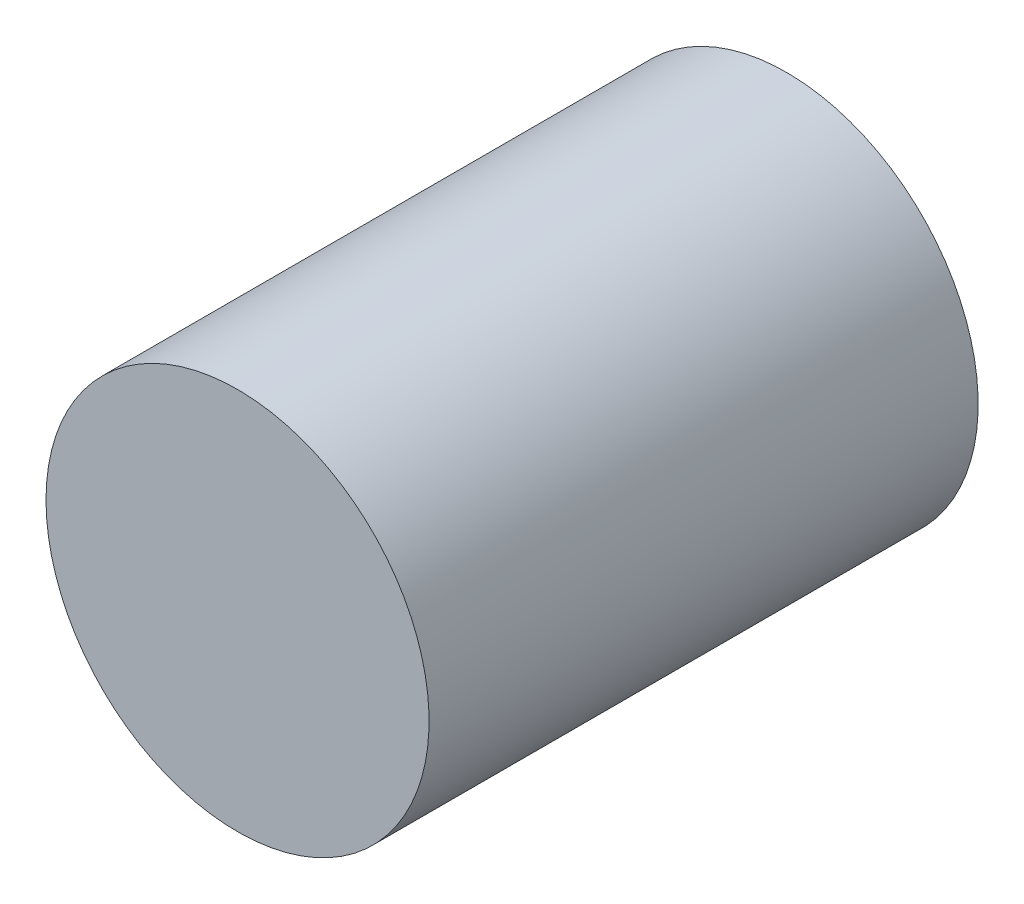
SolidWorks part; units mm, degrees
ref_plane "Front Plane" through (0, 0, 0) normal (0, 0, 1) x (1, 0, 0)
ref_plane "Top Plane" through (0, 0, 0) normal (0, 1, 0) x (1, 0, 0)
ref_plane "Right Plane" through (0, 0, 0) normal (1, 0, 0) x (0, 0, -1)
sketch "Sketch1" plane through (0, 0, 0) normal (0, 0, 1) x (1, 0, 0)
  circle A0 centre (0, 0) radius 3
  dimension "D1" = 6
extrude "Boss-Extrude1" add sketch "Sketch1" along normal blind 8.6
